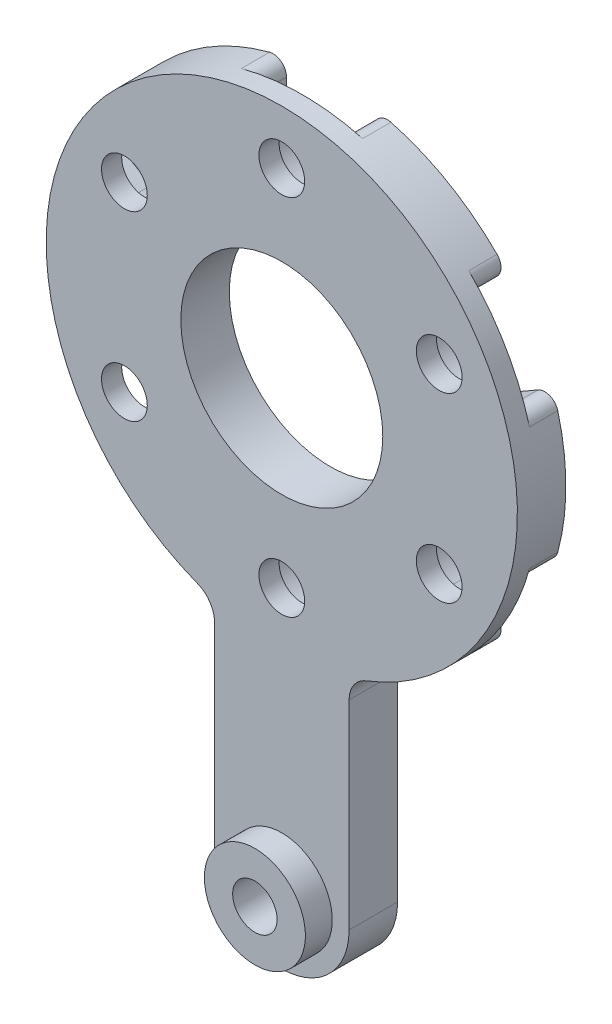
SolidWorks part; units mm, degrees
ref_plane "前视基准面" through (0, 0, 0) normal (0, 0, 1) x (1, 0, 0)
ref_plane "上视基准面" through (0, 0, 0) normal (0, 1, 0) x (1, 0, 0)
ref_plane "右视基准面" through (0, 0, 0) normal (1, 0, 0) x (0, 0, -1)
ref_plane "基准面1" through (0, 0, 0) normal (0, 0, -1) x (-1, 0, 0)
sketch "草图1" plane through (0, 0, 0) normal (0, 0, -1) x (-1, 0, 0)
  line L0 (5, 0) -> (5, 16.2295)
  line L1 (-5, 16.2295) -> (-5, 0)
  arc A0 (5, 16.2295) -> (-5, 16.2295) centre (0, 33) ccw
  arc A1 (-5, 0) -> (5, 0) centre (0, 0) ccw
extrude "凸台-拉伸1" add sketch "草图1" against normal blind 3.6
sketch "草图2" plane through (0, 0, 0) normal (0, 0, -1) x (-1, 0, 0)
  line L0 (15.4323, 27.843) -> (13.3163, 29.0646)
  line L1 (10.0663, 23.4354) -> (12.1823, 22.2138)
  arc A0 (16.8979, 28.4489) -> (15.4323, 27.843) centre (15.9323, 28.709) cw
  arc A1 (13.3163, 29.0646) -> (10.0663, 23.4354) centre (11.6913, 26.25) ccw
  arc A2 (12.1823, 22.2138) -> (12.3903, 20.6416) centre (11.6823, 21.3478) cw
  arc A3 (12.3903, 20.6416) -> (16.8979, 28.4489) centre (0, 33) ccw
extrude "切除-拉伸1" cut sketch "草图2" against normal blind 2.1
sketch "草图3" plane through (0, 0, 0) normal (0, 0, -1) x (-1, 0, 0)
  line L0 (12.1823, 43.7862) -> (10.0663, 42.5646)
  line L1 (13.3163, 36.9354) -> (15.4323, 38.157)
  arc A0 (12.3903, 45.3584) -> (12.1823, 43.7862) centre (11.6823, 44.6522) cw
  arc A1 (10.0663, 42.5646) -> (13.3163, 36.9354) centre (11.6913, 39.75) ccw
  arc A2 (15.4323, 38.157) -> (16.8979, 37.5511) centre (15.9323, 37.291) cw
  arc A3 (16.8979, 37.5511) -> (12.3903, 45.3584) centre (0, 33) ccw
extrude "切除-拉伸2" cut sketch "草图3" against normal blind 2.1
sketch "草图4" plane through (0, 0, 0) normal (0, 0, -1) x (-1, 0, 0)
  line L0 (-3.25, 48.9433) -> (-3.25, 46.5)
  line L1 (3.25, 46.5) -> (3.25, 48.9433)
  arc A0 (-4.5076, 49.9095) -> (-3.25, 48.9433) centre (-4.25, 48.9433) cw
  arc A1 (-3.25, 46.5) -> (3.25, 46.5) centre (0, 46.5) ccw
  arc A2 (3.25, 48.9433) -> (4.5076, 49.9095) centre (4.25, 48.9433) cw
  arc A3 (4.5076, 49.9095) -> (-4.5076, 49.9095) centre (0, 33) ccw
extrude "切除-拉伸3" cut sketch "草图4" against normal blind 2.1
sketch "草图5" plane through (0, 0, 0) normal (0, 0, -1) x (-1, 0, 0)
  line L0 (-15.4323, 38.157) -> (-13.3163, 36.9354)
  line L1 (-10.0663, 42.5646) -> (-12.1823, 43.7862)
  arc A0 (-16.8979, 37.5511) -> (-15.4323, 38.157) centre (-15.9323, 37.291) cw
  arc A1 (-13.3163, 36.9354) -> (-10.0663, 42.5646) centre (-11.6913, 39.75) ccw
  arc A2 (-12.1823, 43.7862) -> (-12.3903, 45.3584) centre (-11.6823, 44.6522) cw
  arc A3 (-12.3903, 45.3584) -> (-16.8979, 37.5511) centre (0, 33) ccw
extrude "切除-拉伸4" cut sketch "草图5" against normal blind 2.1
sketch "草图6" plane through (0, 0, 0) normal (0, 0, -1) x (-1, 0, 0)
  line L0 (-12.1823, 22.2138) -> (-10.0663, 23.4354)
  line L1 (-13.3163, 29.0646) -> (-15.4323, 27.843)
  arc A0 (-12.3903, 20.6416) -> (-12.1823, 22.2138) centre (-11.6823, 21.3478) cw
  arc A1 (-10.0663, 23.4354) -> (-13.3163, 29.0646) centre (-11.6913, 26.25) ccw
  arc A2 (-15.4323, 27.843) -> (-16.8979, 28.4489) centre (-15.9323, 28.709) cw
  arc A3 (-16.8979, 28.4489) -> (-12.3903, 20.6416) centre (0, 33) ccw
extrude "切除-拉伸5" cut sketch "草图6" against normal blind 2.1
ref_plane "基准面2" through (0, 0, 0) normal (0, -1, 0) x (1, 0, 0)
sketch "草图7" plane through (0, 0, 0) normal (0, -1, 0) x (1, 0, 0)
  line L0 (3.75, 5.6) -> (0, 5.6)
  line L1 (0, 5.6) -> (0, 3.6)
  line L2 (0, 3.6) -> (3.75, 3.6)
  line L3 (3.75, 3.6) -> (3.75, 5.6)
  line L4 (0, 5.6) -> (0, 3.6) construction
revolve "旋转1" add sketch "草图7" angle 360 about L4
hole_wizard "M3 六角头机械螺钉的柱形沉头孔1" positions "草图9" profile "草图8" counterbore size "M3" standard "ANSI Metric"
sketch "草图9" plane through (0, 0, 0) normal (0, 0, -1) x (-1, 0, 0)
  point P0 (0, 0)
sketch "草图8" plane through (0, 0, 0) normal (1, 0, 0) x (0, 1, 0)
  line L0 (0, 0) -> (0, 5.6)
  line L1 (0, 5.6) -> (1.65, 5.6)
  line L3 (1.65, 5.6) -> (1.65, 0.8)
  line L4 (1.65, 0.8) -> (3, 0.8)
  line L5 (3, 0.8) -> (3, 0)
  line L7 (3, 0) -> (0, 0)
  line L11 (0, -6.35) -> (0, 107.95) construction
  dimension "通孔孔直径" = 3.3
  dimension "通孔孔深度" = 5.6
  dimension "柱形沉头孔直径" = 6
  dimension "柱形沉头孔深度" = 0.8
hole_wizard "Ø3.4 (3.4) 直径孔1" positions "草图11" profile "草图10" hole size "Ø3.4" standard "ANSI Metric"
sketch "草图11" plane through (0, 0, 3.6) normal (0, 0, 1) x (1, 0, 0)
  point P0 (-11.6913, 26.25)
  point P1 (-11.6913, 39.75)
  point P2 (0, 46.5)
  point P3 (11.6913, 39.75)
  point P4 (11.6913, 26.25)
sketch "草图10" plane through (-11.6913, 26.25, 3.6) normal (1, 0, 0) x (0, -1, 0)
  line L0 (0, 0) -> (0, 3.6)
  line L1 (0, 3.6) -> (1.7, 3.6)
  line L2 (1.7, 3.6) -> (1.7, 0)
  line L5 (1.7, 0) -> (0, 0)
  line L11 (0, -6.35) -> (0, 107.95) construction
  dimension "通孔孔直径" = 3.4
  dimension "通孔孔深度" = 3.6
hole_wizard "M3 六角头机械螺钉的柱形沉头孔2" positions "草图13" profile "草图12" counterbore size "M3" standard "ANSI Metric"
sketch "草图13" plane through (0, 0, 0) normal (0, 0, -1) x (-1, 0, 0)
  point P0 (0, 19.5)
sketch "草图12" plane through (0, 19.5, 0) normal (1, 0, 0) x (0, 1, 0)
  line L0 (0, 0) -> (0, 5.6)
  line L1 (0, 5.6) -> (1.7, 5.6)
  line L3 (1.7, 5.6) -> (1.7, 2.1)
  line L4 (1.7, 2.1) -> (3.25, 2.1)
  line L5 (3.25, 2.1) -> (3.25, 0)
  line L7 (3.25, 0) -> (0, 0)
  line L11 (0, -6.35) -> (0, 107.95) construction
  dimension "通孔孔直径" = 3.4
  dimension "通孔孔深度" = 5.6
  dimension "柱形沉头孔直径" = 6.5
  dimension "柱形沉头孔深度" = 2.1
hole_wizard "Ø15.0 (15) 直径孔1" positions "草图15" profile "草图14" hole size "Ø15.0" standard "ANSI Metric"
sketch "草图15" plane through (0, 0, 3.6) normal (0, 0, 1) x (1, 0, 0)
  point P0 (0, 33)
sketch "草图14" plane through (0, 33, 3.6) normal (1, 0, 0) x (0, -1, 0)
  line L0 (0, 0) -> (0, 3.6)
  line L1 (0, 3.6) -> (7.5, 3.6)
  line L2 (7.5, 3.6) -> (7.5, 0)
  line L5 (7.5, 0) -> (0, 0)
  line L11 (0, -6.35) -> (0, 107.95) construction
  dimension "通孔孔直径" = 15
  dimension "通孔孔深度" = 3.6
fillet "圆角1" radius 2 2 edges at (5, 16.2295, 1.8) (-5, 16.2295, 1.8)
